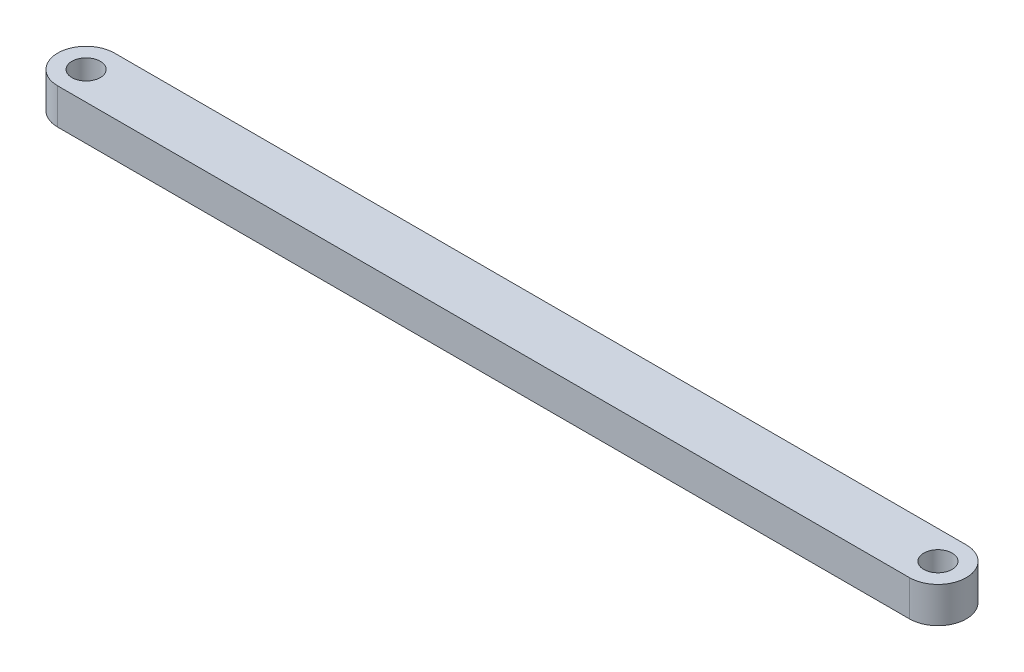
SolidWorks part; units mm, degrees
ref_plane "Front Plane" through (0, 0, 0) normal (0, 0, 1) x (1, 0, 0)
ref_plane "Top Plane" through (0, 0, 0) normal (0, 1, 0) x (1, 0, 0)
ref_plane "Right Plane" through (0, 0, 0) normal (1, 0, 0) x (0, 0, -1)
sketch "Sketch1" plane through (0, 0, 0) normal (0, 1, 0) x (1, 0, 0)
  line L0 (-95.25, 7.62) -> (-95.25, 2.54) construction
  line L1 (-95.25, 2.54) -> (-19.05, 2.54)
  line L2 (-19.05, 7.62) -> (-19.05, 2.54) construction
  line L3 (-95.25, 7.62) -> (-19.05, 7.62)
  arc A0 (-95.25, 7.62) -> (-95.25, 2.54) centre (-95.25, 5.08) ccw
  circle A1 centre (-95.25, 5.08) radius 1.27
  arc A2 (-19.05, 2.54) -> (-19.05, 7.62) centre (-19.05, 5.08) ccw
  circle A3 centre (-19.05, 5.08) radius 1.27
  point P0 (0, 0)
  dimension "D3" = 2.54
  dimension "D2" = 76.2
  dimension "D1" = 5.08
extrude "Boss-Extrude1" add sketch "Sketch1" along normal blind 3.2004 contours L1 A2 L3 A0 A3 A1
